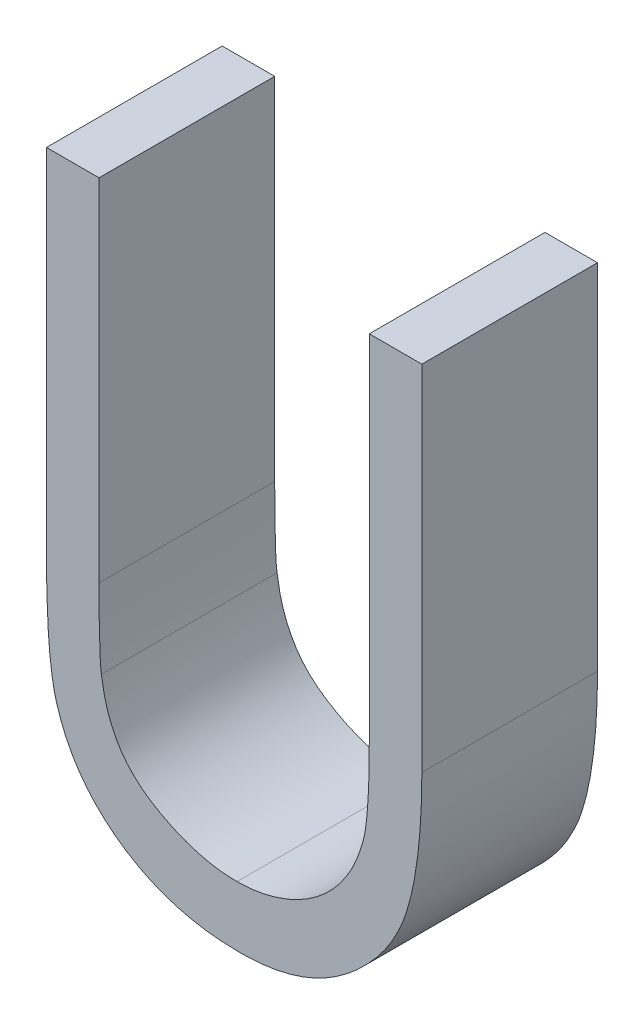
SolidWorks part; units mm, degrees
ref_plane "Plan de face" through (0, 0, 0) normal (0, 0, 1) x (1, 0, 0)
ref_plane "Plan de dessus" through (0, 0, 0) normal (0, 1, 0) x (1, 0, 0)
ref_plane "Plan de droite" through (0, 0, 0) normal (1, 0, 0) x (0, 0, -1)
sketch "Esquisse1" plane through (0, 0, 0) normal (0, 0, 1) x (1, 0, 0)
  text T0 "U" font "Century Gothic" height 5
extrude "Boss.-Extru.1" add sketch "Esquisse1" along normal blind 1.5
